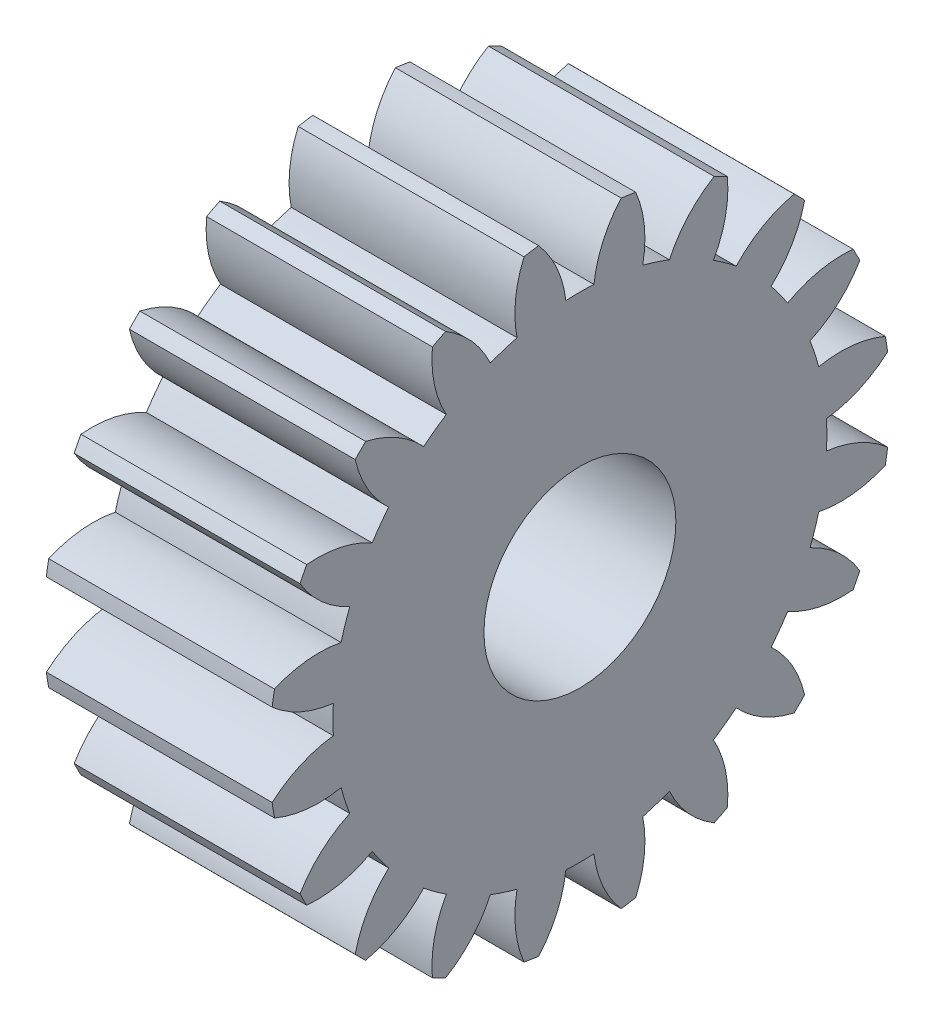
SolidWorks part; units mm, degrees
ref_plane "Plane1" through (0, 0, 0) normal (0, 0, 1) x (1, 0, 0)
ref_plane "Plane2" through (0, 0, 0) normal (0, 1, 0) x (1, 0, 0)
ref_plane "Plane3" through (0, 0, 0) normal (1, 0, 0) x (0, 0, -1)
sketch "HoldingSke" plane through (0, 0, 0) normal (0, 1, 0) x (1, 0, 0)
  line L0 (0, 0) -> (0.7518, -0.2736)
  line L1 (-15, 0) -> (100, 0) construction
  line L2 (0, 0) -> (-2.1039, 2.3779)
  line L3 (0, 0) -> (-11.863, 4.5341)
  line L4 (0, 0) -> (8.1152, 2.9537)
  line L5 (0, 0) -> (-46.8476, -17.4728)
  line L6 (0, 0) -> (-8.2896, -5.593)
  line L7 (-2.1039, 2.3779) -> (8.6586, 51.2059)
  line L8 (-76.2, 54.61) -> (-75.5, 54.61)
  line L9 (-71.009, 38.7566) -> (-53.1078, 45.2721)
  line L10 (-76.2, 71.12) -> (104.1128, 71.12)
  line L11 (0, 0) -> (-10, 0)
  line L12 (-76.2, 101.6) -> (-76.155, 101.6)
  line L13 (24.9733, 27.94) -> (52.9518, 28.4284)
  line L14 (24.9733, 27.94) -> (24.9743, 27.94)
  line L15 (24.9733, 27.94) -> (100.4006, 29.5858)
  line L16 (-63.627, -1.25) -> (-12.827, -1.25)
  circle A0 centre (0, 0) radius 2
  circle A1 centre (0, 0) radius 10.9365
  circle A2 centre (0, 0) radius 37.5
  circle A3 centre (0, 0) radius 2
  dimension "MHD" = 21.873
  dimension "Hub_dia" = 75
  dimension "Bore" = 4
  dimension "MBD" = 4
  dimension "Num_teeth" = 20
  dimension "Pitch" = 0.8
  dimension "Overall_len" = 50
  dimension "Show_teeth" = 20
  dimension "Thickness" = 10
  dimension "OAL" = 50.0001
  dimension "T_dim" = 0.7
  dimension "Ap" = 20
  dimension "H" = 19.05
  dimension "Pitch_radius" = 180.3128
  dimension "Width" = 10
  dimension "Backlash" = 0.045
  dimension "Addendum_fac" = 1
  dimension "Dedendum_fac" = 1.25
  dimension "Clearance_fac" = 0.25
  dimension "Dedendum_add" = 0.001
  dimension "Module" = 1.25
sketch "BasProSke" plane through (0, 0, 0) normal (0, 1, 0) x (1, 0, 0)
  line L0 (-10, 0) -> (60, 0) construction
  line L1 (0, 0) -> (0, 13.75)
  line L2 (0, 0) -> (10, 0)
  line L3 (10, 0) -> (10, 13.75)
  line L4 (10, 13.75) -> (0, 13.75)
  dimension "Thickness" = 10
  dimension "Diameter" = 27.5
revolve "Base-Revolve" add sketch "BasProSke" angle 360 about L0
sketch "TooCutSke" plane through (0, 0, 0) normal (1, 0, 0) x (0, 0, -1)
  line L1 (0, 0) -> (0, 107) construction
  line L2 (0, 0) -> (-1.0594, 12.455) construction
  line L3 (0, 0) -> (-3.9007, 24.6278) construction
  line L4 (-1.0594, 12.455) -> (-1.9503, 12.3139) construction
  arc A0 (0.6211, 10.9188) -> (-0.6211, 10.9188) centre (0, 0) ccw
  arc A1 (1.8466, 13.6511) -> (-1.8466, 13.6511) centre (0, 0) ccw
  circle A2 centre (0, 0) radius 12.5 construction
  circle A3 centre (0, 0) radius 11.7462 construction
  arc A4 (-0.6211, 10.9188) -> (-1.8466, 13.6511) centre (-5.5866, 10.3326) ccw
  arc A5 (1.8466, 13.6511) -> (0.6211, 10.9188) centre (5.5866, 10.3326) ccw
  dimension "Root_dia" = 21.873
  dimension "Overcut_dia" = 27.5508
  dimension "Pitch_dia" = 25
  dimension "Base_dia" = 23.4923
  dimension "Flank_rad" = 5
  dimension "Half_ang" = 9
  dimension "Half_CT" = 0.902
extrude "ToothCut" cut sketch "TooCutSke" along normal through all
fillet "Breaks" [suppressed] radius 0.025
fillet "RootFillets" [suppressed] radius 0.3135
pattern_circular "TeethCuts" count 20 every 18 about axis through (-10, 0, 0) along (1, 0, 0) of "ToothCut", "RootFillets", "Breaks"
sketch "HubNeaOneSke" plane through (0, 0, 0) normal (-1, 0, 0) x (0, 0, 1)
  circle A0 centre (0, 0) radius 10.9365
  dimension "Diameter" = 21.873
extrude "HubNearOne" [suppressed] add sketch "HubNeaOneSke" along normal blind 40.0001
sketch "HubNeaBotSke" plane through (0, 0, 0) normal (-1, 0, 0) x (0, 0, 1)
  circle A0 centre (0, 0) radius 10.9365
  dimension "Diameter" = 21.873
extrude "HubNearBoth" [suppressed] add sketch "HubNeaBotSke" along normal blind 20
ref_plane "FarPln" through (10, 0, 0) normal (1, 0, 0) x (0, 0, -1)
sketch "HubFarSke" plane through (10, 0, 0) normal (1, 0, 0) x (0, 0, -1)
  circle A0 centre (0, 0) radius 10.9365
  dimension "Diameter" = 21.873
extrude "HubFar" [suppressed] add sketch "HubFarSke" along normal blind 20
sketch "BorSke" plane through (0, 0, 0) normal (1, 0, 0) x (0, 0, -1)
  circle A0 centre (0, 0) radius 2
  dimension "Diameter" = 4
extrude "Bore" cut sketch "BorSke" along normal mid plane 100.0001
sketch "KeySke" plane through (0, 0, 0) normal (1, 0, 0) x (0, 0, -1)
  line L0 (-0.8, 0) -> (-0.8, 2.7)
  line L1 (-0.8, 2.7) -> (0.8, 2.7)
  line L2 (0.8, 2.7) -> (0.8, 0)
  line L3 (0, 0) -> (0, 34) construction
  line L4 (-0.8, 0) -> (0.8, 0)
  dimension "Offset" = 2.7
  dimension "Width" = 1.6
extrude "Keyway" [suppressed] cut sketch "KeySke" along normal mid plane 100.0001
pattern_circular "Keyway2" [suppressed] count 2 every 90 about axis through (-10, 0, 0) along (1, 0, 0)
sketch "Sketch1" plane through (10, 0, 0) normal (1, 0, 0) x (0, 0, -1)
sketch "Sketch2" plane through (10, 0, 0) normal (1, 0, 0) x (0, 0, -1)
  circle A0 centre (0, 0) radius 2
extrude "Boss-Extrude1" add sketch "Sketch2" against normal blind 10
sketch "Sketch3" plane through (10, 0, 0) normal (1, 0, 0) x (0, 0, -1)
  circle A0 centre (0, 0) radius 4.25
  dimension "D1" = 8.5
extrude "Cut-Extrude2" cut sketch "Sketch3" against normal blind 10
equation "' \"Module@HoldingSke\" = 6.35"
equation "' \"Num_teeth@HoldingSke\" = 12"
equation "' \"Ap@HoldingSke\" =  20"
equation "' \"Ap@HoldingSke\" = 20"
equation "' \"Width@HoldingSke\" = 0.5 * 25.4"
equation "' \"Hub_dia@HoldingSke\"= 1 * 25.4"
equation "' \"Hub_dia@HoldingSke\" = 1 * 25.4"
equation "' \"Overall_len@HoldingSke\" = 1.0 * 25.4"
equation "' \"Bore@HoldingSke\" = 0.75 * 25.4"
equation "' \"T_dim@HoldingSke\" = 0.1 * 25.4"
equation "' \"Width@KeySke\" = 0.25 * 25.4"
equation "' \"Show_teeth@HoldingSke\" = 13"
equation "' \"Backlash@HoldingSke\" = 0.009 * 25.4"
equation "' \"Addendum_fac@HoldingSke\" = 1.0"
equation "' \"Dedendum_fac@HoldingSke\" = 1.25"
equation "' \"Dedendum_add@HoldingSke\" = 0.00005 * 25.4"
equation "' \"Clearance_fac@HoldingSke\" = 0.25"
equation "\"Pitch@HoldingSke\" = 1 / \"Module@HoldingSke\""
equation "\"Overcut_dia@TooCutSke\" = (\"Num_teeth@HoldingSke\" + 2 * \"Addendum_fac@HoldingSke\") / \"Pitch@HoldingSke\" + 0.002 * 25.4"
equation "\"Pitch_dia@TooCutSke\" = \"Num_teeth@HoldingSke\" / \"Pitch@HoldingSke\""
equation "\"Base_dia@TooCutSke\" = \"Num_teeth@HoldingSke\" / \"Pitch@HoldingSke\" * cos((\"Ap@HoldingSke\"  * 3.14159265 / 180))"
equation "\"Root_dia@TooCutSke\" = (\"Num_teeth@HoldingSke\" + 2) / \"Pitch@HoldingSke\" - 2 * (\"Addendum_fac@HoldingSke\" + \"Dedendum_fac@HoldingSke\") / \"Pitch@HoldingSke\" - \"Dedendum_add@HoldingSke\" * 2"
equation "\"Half_ang@TooCutSke\" = 180 / \"Num_teeth@HoldingSke\""
equation "\"Half_CT@TooCutSke\" = \"Num_teeth@HoldingSke\" / \"Pitch@HoldingSke\" * sin((3.14159265 / 2 / \"Num_teeth@HoldingSke\")) / 2 - 7 * \"Backlash@HoldingSke\" / 4"
equation "\"Flank_rad@TooCutSke\" = \"Num_teeth@HoldingSke\" / \"Pitch@HoldingSke\" / 5"
equation "\"Radius@RootFillets\" = \"Clearance_fac@HoldingSke\" / \"Pitch@HoldingSke\" + \"Dedendum_add@HoldingSke\""
equation "\"Break_rad@Breaks\" = 0.02 / \"Pitch@HoldingSke\""
equation "\"Thickness@HoldingSke\" = \"Width@HoldingSke\""
equation "\"OAL@HoldingSke\" = \"Thickness@HoldingSke\""
equation "\"MHD@HoldingSke\" = (\"Num_teeth@HoldingSke\" + 2) / \"Pitch@HoldingSke\" - 2 * (\"Addendum_fac@HoldingSke\" + \"Dedendum_fac@HoldingSke\")  / \"Pitch@HoldingSke\" - \"Dedendum_add@HoldingSke\" * 2"
equation "\"MBD@HoldingSke\" = (\"Num_teeth@HoldingSke\" + 2) / \"Pitch@HoldingSke\" - 2 * (\"Addendum_fac@HoldingSke\" + \"Dedendum_fac@HoldingSke\")  / \"Pitch@HoldingSke\" - \"Dedendum_add@HoldingSke\" * 2 - 0.002 * 25.4"
equation "\"MHD@HoldingSke\" = ((sgn( \"MHD@HoldingSke\" - \"Hub_dia@HoldingSke\" )-1)*( \"MHD@HoldingSke\" - \"Hub_dia@HoldingSke\" ))/-2+ \"Hub_dia@HoldingSke\""
equation "\"MBD@HoldingSke\" = ((sgn( \"MBD@HoldingSke\" - \"Bore@HoldingSke\" )-1)*( \"MBD@HoldingSke\" - \"Bore@HoldingSke\" ))/-2+ \"Bore@HoldingSke\""
equation "\"OAL@HoldingSke\" = ((sgn( \"OAL@HoldingSke\" - \"Overall_len@HoldingSke\" )+1)*( \"OAL@HoldingSke\" - \"Overall_len@HoldingSke\" ))/2 + \"Overall_len@HoldingSke\" + 0.000002 * 25.4"
equation "\"Num_teeth@TeethCuts\" = int( \"Show_teeth@HoldingSke\" ) + 1"
equation "\"Num_teeth@TeethCuts\" = ((sgn( \"Num_teeth@TeethCuts\" - \"Num_teeth@HoldingSke\" )-1)*( \"Num_teeth@TeethCuts\" - \"Num_teeth@HoldingSke\" ))/-2+ \"Num_teeth@HoldingSke\""
equation "\"Num_teeth@TeethCuts\" = ((sgn( \"Num_teeth@TeethCuts\" - 2.0)+1)*( \"Num_teeth@TeethCuts\" - 2.0))/2 +2.0"
equation "\"Angle@TeethCuts\" = 360.0 / \"Num_teeth@HoldingSke\""
equation "\"Diameter@BasProSke\" = (\"Num_teeth@HoldingSke\" + 2 * \"Addendum_fac@HoldingSke\") / \"Pitch@HoldingSke\""
equation "\"Thickness@BasProSke\"  = \"Thickness@HoldingSke\""
equation "' \"Fillet_rad@BasProSke\" =  \"Thickness@HoldingSke\" * 0.05"
equation "' \"Fillet_rad@BasProSke\" = \"Thickness@HoldingSke\" * 0.05"
equation "\"MHD@HoldingSke\" = ((sgn( \"MHD@HoldingSke\" - \"Root_dia@TooCutSke\" )-1)*( \"MHD@HoldingSke\" - \"Root_dia@TooCutSke\" ))/-2+ \"Root_dia@TooCutSke\""
equation "\"Diameter@HubNeaOneSke\" = \"MHD@HoldingSke\""
equation "\"Length@HubNearOne\" = \"OAL@HoldingSke\" - \"Thickness@BasProSke\""
equation "\"Diameter@HubNeaBotSke\" = \"MHD@HoldingSke\""
equation "\"Length@HubNearBoth\" = ( \"OAL@HoldingSke\" - \"Thickness@BasProSke\" ) / 2.0"
equation "\"Thickness@FarPln\" = \"Thickness@BasProSke\""
equation "\"Diameter@HubFarSke\" = \"MHD@HoldingSke\""
equation "\"Length@HubFar\" = ( \"OAL@HoldingSke\" - \"Thickness@BasProSke\" ) / 2.0"
equation "\"Diameter@BorSke\" = \"MBD@HoldingSke\""
equation "\"D1@Bore\" = \"OAL@HoldingSke\" * 2.0"
equation "\"D1@Keyway\" = \"OAL@HoldingSke\" * 2.0"
equation "\"Offset@KeySke\" = \"T_dim@HoldingSke\" + \"MBD@HoldingSke\" / 2.0"
